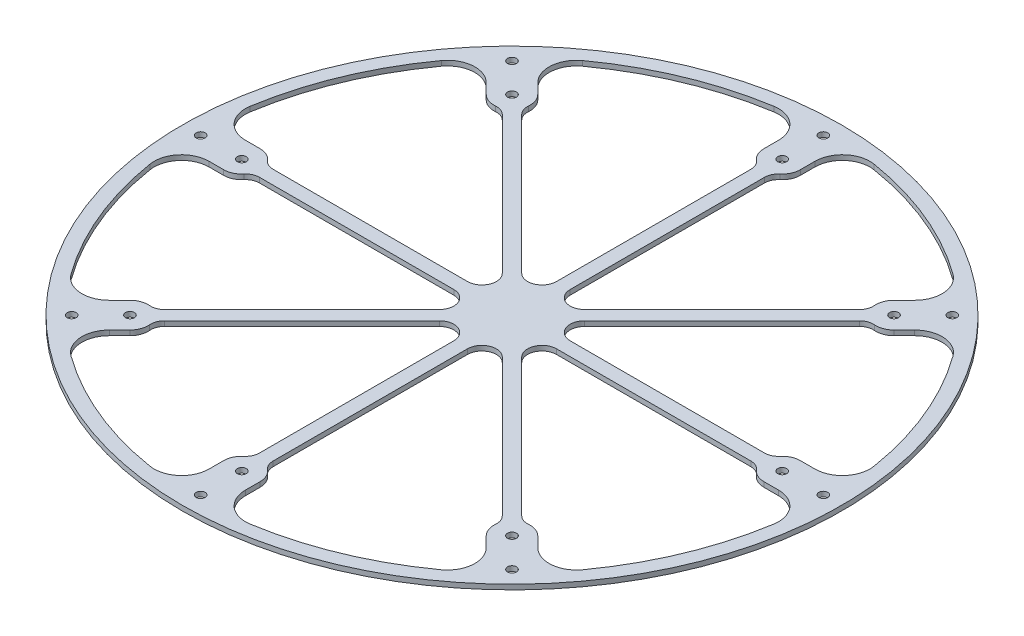
SolidWorks part; units mm, degrees
material "6061-T6 (SS)"
ref_plane "Front Plane" through (0, 0, 0) normal (0, 0, 1) x (1, 0, 0)
ref_plane "Top Plane" through (0, 0, 0) normal (0, 1, 0) x (1, 0, 0)
ref_plane "Right Plane" through (0, 0, 0) normal (1, 0, 0) x (0, 0, -1)
sketch "Sketch1" plane through (0, 0, 0) normal (0, 1, 0) x (1, 0, 0)
  line L0 (0, 0) -> (-152.4, 0) construction
  line L1 (0, 0) -> (-124.9299, 0) construction
  circle A0 centre (0, 0) radius 152.4
  circle A1 centre (-143.9799, 0) radius 2.0701
  circle A2 centre (-124.9299, 0) radius 2.0701
  circle A3 centre (-143.9799, 0) radius 8.4201 construction
  circle A4 centre (-101.8092, 101.8092) radius 8.4201 construction
  circle A5 centre (-101.8092, 101.8092) radius 2.0701
  circle A6 centre (-88.3388, 88.3388) radius 2.0701
  circle A7 centre (0, 143.9799) radius 8.4201 construction
  circle A8 centre (0, 143.9799) radius 2.0701
  circle A9 centre (0, 124.9299) radius 2.0701
  circle A10 centre (101.8092, 101.8092) radius 8.4201 construction
  circle A11 centre (101.8092, 101.8092) radius 2.0701
  circle A12 centre (88.3388, 88.3388) radius 2.0701
  circle A13 centre (143.9799, 0) radius 8.4201 construction
  circle A14 centre (143.9799, 0) radius 2.0701
  circle A15 centre (124.9299, 0) radius 2.0701
  circle A16 centre (101.8092, -101.8092) radius 8.4201 construction
  circle A17 centre (101.8092, -101.8092) radius 2.0701
  circle A18 centre (88.3388, -88.3388) radius 2.0701
  circle A19 centre (0, -143.9799) radius 8.4201 construction
  circle A20 centre (0, -143.9799) radius 2.0701
  circle A21 centre (0, -124.9299) radius 2.0701
  circle A22 centre (-101.8092, -101.8092) radius 8.4201 construction
  circle A23 centre (-101.8092, -101.8092) radius 2.0701
  circle A24 centre (-88.3388, -88.3388) radius 2.0701
  dimension "D1" = 304.8
  dimension "D2" = 4.1402
  dimension "D4" = 6.35
  dimension "D3" = 19.05
  dimension "D6" = 124.9299
  dimension "D5" = 8
extrude "Boss-Extrude1" add sketch "Sketch1" along normal blind 2.286
sketch "Sketch2" plane through (0, 2.286, 0) normal (0, 1, 0) x (1, 0, 0)
  line L0 (0, 0) -> (0, -152.4) construction
  line L1 (0, 0) -> (107.7631, -107.7631) construction
  line L2 (8.4201, -124.9299) -> (8.4201, -143.9799)
  line L3 (0, 0) -> (58.321, -140.7992) construction
  line L4 (11.0369, -15.527) -> (94.0497, -98.5398)
  line L5 (82.3849, -94.2927) -> (95.8553, -107.7631)
  line L6 (3.175, -18.7836) -> (3.175, -136.1813)
  circle A0 centre (0, 0) radius 152.4 construction
  circle A1 centre (101.8092, -101.8092) radius 2.0701 construction
  circle A2 centre (88.3388, -88.3388) radius 2.0701 construction
  circle A3 centre (0, -124.9299) radius 2.0701 construction
  circle A4 centre (0, -143.9799) radius 2.0701 construction
  circle A5 centre (0, 0) radius 152.4
  circle A6 centre (101.8092, -101.8092) radius 2.0701
  circle A7 centre (88.3388, -88.3388) radius 2.0701
  circle A8 centre (0, -124.9299) radius 2.0701
  circle A9 centre (0, -143.9799) radius 2.0701
  circle A10 centre (0, -124.9299) radius 8.4201
  circle A11 centre (0, -143.9799) radius 8.4201
  circle A12 centre (101.8092, -101.8092) radius 8.4201
  circle A13 centre (88.3388, -88.3388) radius 8.4201
  circle A14 centre (0, 0) radius 146.05
  circle A15 centre (0, 0) radius 19.05
  arc A16 (8.4201, -131.6669) -> (23.1315, -144.2066) centre (21.1201, -131.6669) ccw
  arc A17 (87.1486, -99.0564) -> (85.613, -118.3259) centre (78.1684, -108.0367) cw
  arc A18 (14.5548, -19.0449) -> (3.175, -23.7586) centre (9.8411, -23.7586) ccw
  dimension "D2" = 38.1
  dimension "D4" = 25.4
  dimension "D3" = 3.175
  dimension "D5" = 22.5
  dimension "D1" = 6.35
extrude "Cut-Extrude1" cut sketch "Sketch2" against normal through all contours L4 A18 L6 A10 L2 A16 A14 A17 L5 A13
pattern_circular "CirPattern1" count 8 every 45 about axis through (0, 0, 0) along (0, 1, 0) of "Cut-Extrude1"
fillet "Fillet1" radius 6.35 16 edges at (3.175, 1.143, -117.1313) (-3.175, 1.143, -117.1313) (-80.5793, 1.143, -85.0694) (-85.0694, 1.143, -80.5793) (-117.1313, 1.143, -3.175) (-117.1313, 1.143, 3.175) (-80.5793, 1.143, 85.0694) (-85.0694, 1.143, 80.5793) (-3.175, 1.143, 117.1313) (3.175, 1.143, 117.1313) (85.0694, 1.143, 80.5793) (80.5793, 1.143, 85.0694) (117.1313, 1.143, 3.175) (117.1313, 1.143, -3.175) (80.5793, 1.143, -85.0694) (85.0694, 1.143, -80.5793)
